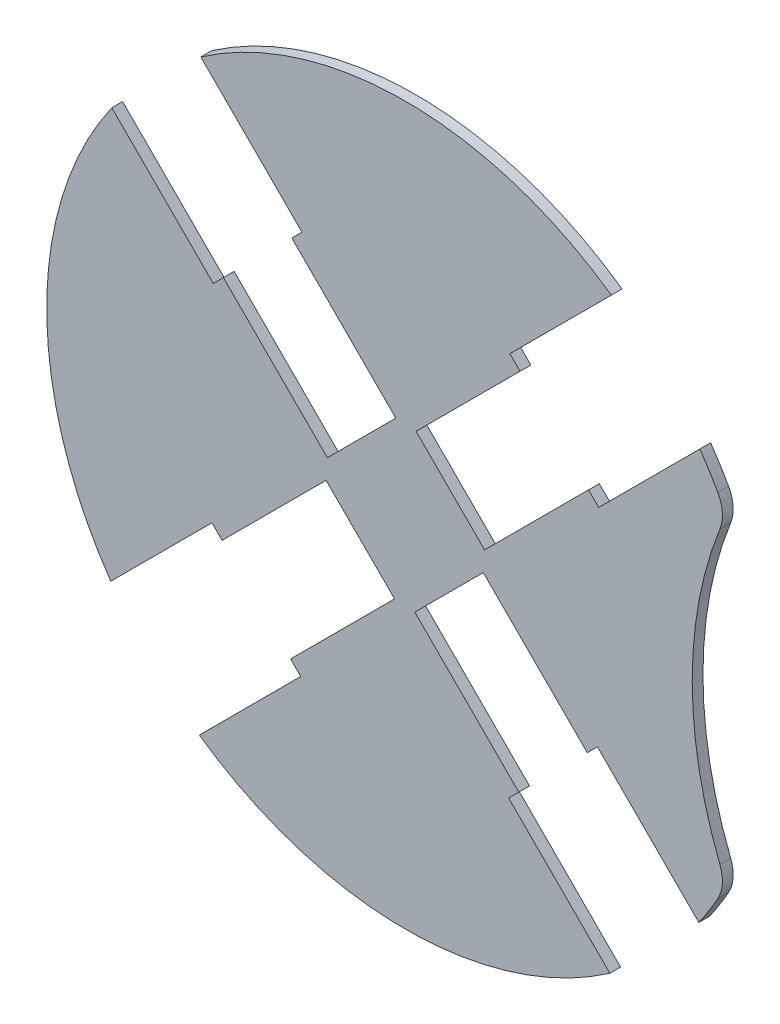
SolidWorks part; units mm, degrees
ref_plane "Alzado" through (0, 0, 0) normal (0, 0, 1) x (1, 0, 0)
ref_plane "Planta" through (0, 0, 0) normal (0, 1, 0) x (1, 0, 0)
ref_plane "Vista lateral" through (0, 0, 0) normal (1, 0, 0) x (0, 0, -1)
sketch "Croquis1" plane through (0, 0, 0) normal (0, 0, 1) x (1, 0, 0)
  circle A0 centre (0, 0) radius 100
  dimension "D1" = 200
extrude "Saliente-Extruir1" add sketch "Croquis1" along normal blind 3
sketch "Croquis3" plane through (0, 0, 3) normal (0, 0, 1) x (1, 0, 0)
  line L0 (0, 0) -> (190, 0) construction
  circle A0 centre (190, 0) radius 110
  dimension "D1" = 220
  dimension "D2" = 190
extrude "Cortar-Extruir1" cut sketch "Croquis3" against normal blind 3
fillet "Redondeo1" radius 10 2 edges at (89.4737, -44.6594, 1.5) (89.4737, 44.6594, 1.5)
sketch "Croquis4" plane through (0, 0, 3) normal (0, 0, 1) x (1, 0, 0)
  line L0 (0, -100) -> (-100, 0) construction
  line L1 (-50, -50) -> (-70.7107, -70.7107) construction
  line L2 (-70.7107, -70.7107) -> (-58.5131, -82.9083) construction
  line L3 (-58.5131, -82.9083) -> (-83.2618, -58.1595)
  line L4 (-58.5131, -82.9083) -> (-29.1682, -53.5633)
  line L5 (-53.9169, -28.8146) -> (-51.0885, -31.643)
  line L6 (-53.9169, -28.8146) -> (-83.2618, -58.1595)
  line L7 (-50, -50) -> (-41.5405, -41.1909) construction
  line L8 (-82.9083, 58.5131) -> (-53.5633, 29.1682)
  line L9 (-41.5405, -41.1909) -> (-13.142, -11.6186) construction
  line L10 (-31.9966, -50.7349) -> (-29.1682, -53.5633)
  line L12 (-31.9966, -50.7349) -> (-3.0052, -21.7435)
  line L13 (-3.0052, -21.7435) -> (-22.0971, -2.6517)
  line L14 (-22.0971, -2.6517) -> (-51.0885, -31.643)
  line L15 (-50.7349, 31.9966) -> (-21.7435, 3.0052)
  line L16 (-50.7349, 31.9966) -> (-53.5633, 29.1682)
  line L17 (-28.8146, 53.9169) -> (-58.1595, 83.2618)
  line L18 (-28.8146, 53.9169) -> (-31.643, 51.0885)
  line L19 (-2.6517, 22.0971) -> (-31.643, 51.0885)
  line L20 (-21.7435, 3.0052) -> (-2.6517, 22.0971)
  line L21 (-82.9083, 58.5131) -> (-58.1595, 83.2618)
  line L22 (58.5131, 82.9083) -> (29.1682, 53.5633)
  line L23 (31.9966, 50.7349) -> (3.0052, 21.7435)
  line L24 (31.9966, 50.7349) -> (29.1682, 53.5633)
  line L25 (53.9169, 28.8146) -> (83.2618, 58.1595)
  line L26 (53.9169, 28.8146) -> (51.0885, 31.643)
  line L27 (22.0971, 2.6517) -> (51.0885, 31.643)
  line L28 (3.0052, 21.7435) -> (22.0971, 2.6517)
  line L29 (58.5131, 82.9083) -> (83.2618, 58.1595)
  line L30 (82.9083, -58.5131) -> (53.5633, -29.1682)
  line L31 (50.7349, -31.9966) -> (21.7435, -3.0052)
  line L32 (50.7349, -31.9966) -> (53.5633, -29.1682)
  line L33 (28.8146, -53.9169) -> (58.1595, -83.2618)
  line L34 (28.8146, -53.9169) -> (31.643, -51.0885)
  line L35 (2.6517, -22.0971) -> (31.643, -51.0885)
  line L36 (21.7435, -3.0052) -> (2.6517, -22.0971)
  line L37 (82.9083, -58.5131) -> (58.1595, -83.2618)
  arc A0 (87.1345, 49.0671) -> (87.1345, -49.0671) centre (0, 0) ccw construction
  point P46 (0, 0)
  dimension "D1" = 29.2893
  dimension "D2" = 35
  dimension "D3" = 17.75
  dimension "D4" = 41.5
  dimension "D5" = 13.5
  dimension "D6" = 27
  dimension "D7" = 27
  dimension "D8" = 41
  dimension "D9" = 17.5
  dimension "D10" = 17.75
  dimension "D11" = 4
  dimension "D12" = 4
extrude "Cortar-Extruir2" cut sketch "Croquis4" against normal through all
